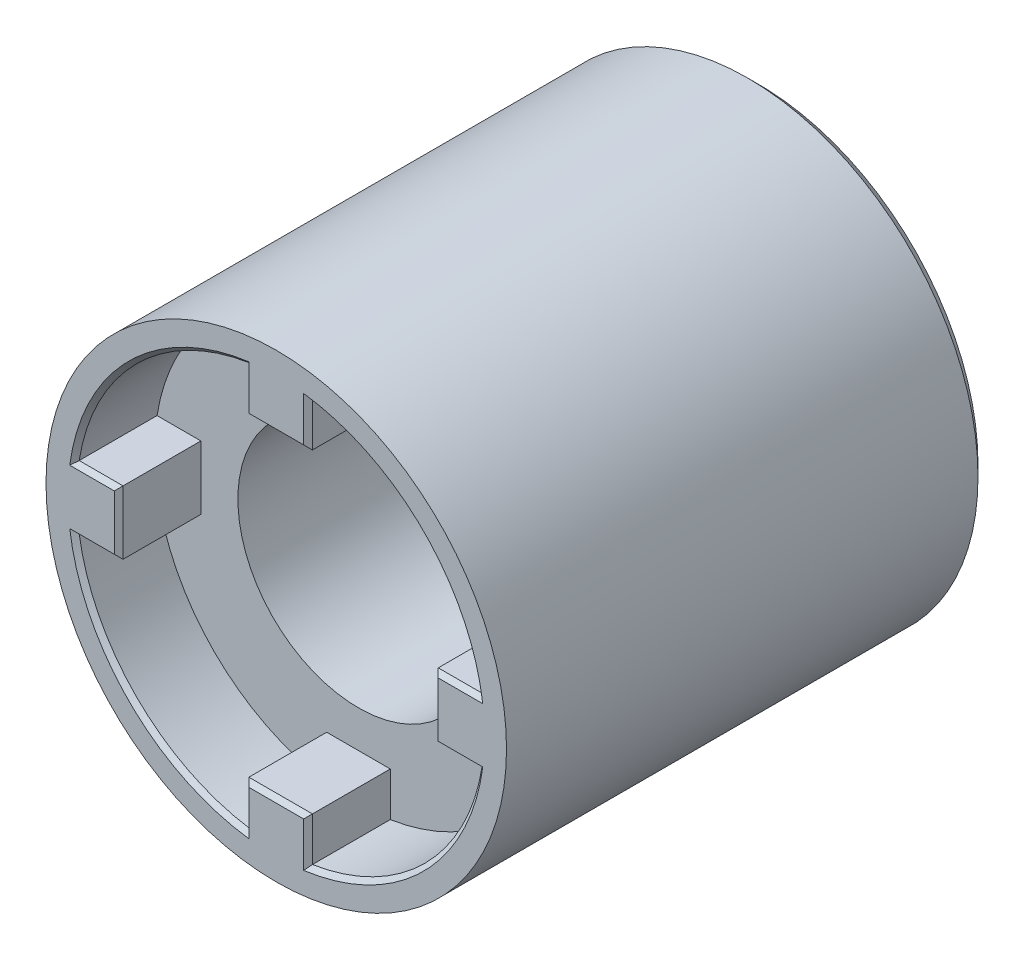
SolidWorks part; units mm, degrees
ref_plane "Front Plane" through (0, 0, 0) normal (0, 0, 1) x (1, 0, 0)
ref_plane "Top Plane" through (0, 0, 0) normal (0, 1, 0) x (1, 0, 0)
ref_plane "Right Plane" through (0, 0, 0) normal (1, 0, 0) x (0, 0, -1)
sketch "Sketch1" plane through (0, 0, 0) normal (0, 0, 1) x (1, 0, 0)
  circle A0 centre (0, 0) radius 10.5
  dimension "D1" = 21
extrude "Boss-Extrude1" add sketch "Sketch1" along normal blind 22
sketch "Sketch2" plane through (0, 0, 22) normal (0, 0, 1) x (1, 0, 0)
  circle A0 centre (0, 0) radius 9.3
  dimension "D1" = 18.6
extrude "Cut-Extrude1" cut sketch "Sketch2" against normal blind 3.75
sketch "Sketch3" plane through (0, 0, 18.25) normal (0, 0, 1) x (1, 0, 0)
  line L0 (-1.45, 9.1863) -> (-1.45, 7.1863)
  line L1 (-1.45, 7.1863) -> (1.45, 7.1863)
  line L2 (1.45, 7.1863) -> (1.45, 9.1863)
  line L3 (1.45, 9.1863) -> (-1.45, 9.1863) construction
  line L4 (7.1863, -1.45) -> (9.1863, -1.45)
  line L5 (7.1863, 1.45) -> (7.1863, -1.45)
  line L6 (9.1863, 1.45) -> (7.1863, 1.45)
  line L7 (-1.45, -7.1863) -> (-1.45, -9.1863)
  line L8 (1.45, -7.1863) -> (-1.45, -7.1863)
  line L9 (1.45, -9.1863) -> (1.45, -7.1863)
  line L10 (-7.1863, 1.45) -> (-9.1863, 1.45)
  line L11 (-7.1863, -1.45) -> (-7.1863, 1.45)
  line L12 (-9.1863, -1.45) -> (-7.1863, -1.45)
  circle A0 centre (0, 0) radius 9.3 construction
  circle A1 centre (0, 0) radius 9.3 construction
  arc A2 (1.45, 9.1863) -> (-1.45, 9.1863) centre (0, 0) ccw
  arc A3 (-1.45, -9.1863) -> (1.45, -9.1863) centre (0, 0) ccw
  arc A4 (-9.1863, 1.45) -> (-9.1863, -1.45) centre (0, 0) ccw
  arc A5 (9.1863, -1.45) -> (9.1863, 1.45) centre (0, 0) ccw
  point P24 (0, 0)
  dimension "D1" = 2.9
  dimension "D2" = 2
  dimension "D3" = 4
extrude "Boss-Extrude3" add sketch "Sketch3" along normal up to surface (3.75 mm away) up to face at (9.3, 0, 22)
chamfer "Chamfer1" distance 0.2 angle 45 16 edges at (-8.1863, 1.45, 22) (-7.1863, 0, 22) (-8.1863, -1.45, 22) (-6.5761, -6.5761, 22) (-1.45, -8.1863, 22) (0, -7.1863, 22) (1.45, -8.1863, 22) (6.5761, -6.5761, 22) (8.1863, -1.45, 22) (7.1863, 0, 22) (8.1863, 1.45, 22) (6.5761, 6.5761, 22) (1.45, 8.1863, 22) (0, 7.1863, 22) (-1.45, 8.1863, 22) (-6.5761, 6.5761, 22)
sketch "Sketch4" plane through (0, 0, 18.25) normal (0, 0, 1) x (1, 0, 0)
  line L1 (-3.3, -3.3) -> (3.3, -3.3)
  line L2 (-3.3, -3.3) -> (-3.3, 3.3)
  line L3 (-3.3, 3.3) -> (3.3, 3.3)
  line L4 (3.3, -3.3) -> (3.3, 3.3)
  line L5 (-3.3, -3.3) -> (3.3, 3.3) construction
  line L6 (-3.3, 3.3) -> (3.3, -3.3) construction
  point P0 (0, 0)
  dimension "D1" = 6.6
extrude "Cut-Extrude2" cut sketch "Sketch4" against normal through all
chamfer "Chamfer2" distance 0.5 angle 45 5 edges at (-3.3, 0, 0) (0, -3.3, 0) (3.3, 0, 0) (0, 3.3, 0) (10.5, 0, 0)
sketch "Sketch5" plane through (0, 0, 0) normal (0, 1, 0) x (1, 0, 0)
  line L0 (3.3, -0.5) -> (3.3, -18.25) construction
  line L1 (-3.8, 0) -> (3.8, 0) construction
  line L2 (3.3, -6.6354) -> (3.3, 3.2908) construction
  line L3 (3.3, -1.5) -> (3.3, -4.5)
  arc A0 (3.3, -4.5) -> (3.3, -1.5) centre (3.3, -3) ccw
  dimension "D1" = 3
  dimension "D2" = 3
revolve "Cut-Revolve1" cut sketch "Sketch5" angle 360 about L2
sketch "Sketch6" plane through (0, 0, 18.25) normal (0, 0, 1) x (1, 0, 0)
  circle A0 centre (0, 0) radius 5.5
  dimension "D1" = 11
extrude "Cut-Extrude3" cut sketch "Sketch6" against normal blind 10
